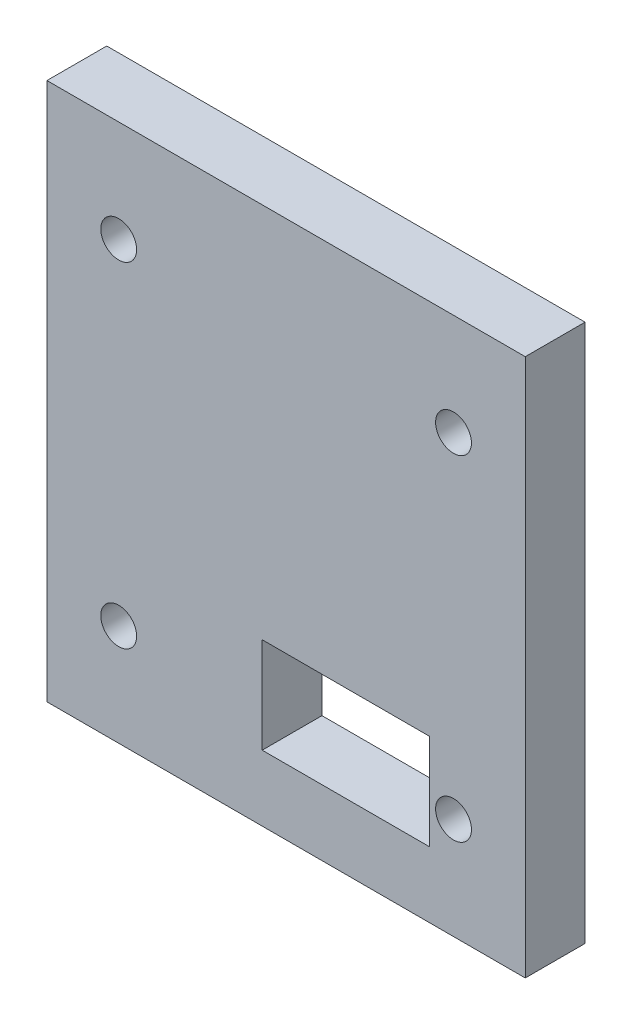
SolidWorks part; units mm, degrees
ref_plane "Front Plane" through (0, 0, 0) normal (0, 0, 1) x (1, 0, 0)
ref_plane "Top Plane" through (0, 0, 0) normal (0, 1, 0) x (1, 0, 0)
ref_plane "Right Plane" through (0, 0, 0) normal (1, 0, 0) x (0, 0, -1)
sketch "Sketch1" plane through (0, 0, 0) normal (0, 0, 1) x (1, 0, 0)
  line L1 (0, 0) -> (35, 0)
  line L2 (0, 0) -> (0, 45)
  line L3 (0, 45) -> (35, 45)
  line L4 (35, 0) -> (35, 45)
  dimension "D1" = 45
  dimension "D2" = 35
extrude "Boss-Extrude1" add sketch "Sketch1" along normal blind 5
sketch "Sketch2" plane through (0, 0, 0) normal (0, -1, 0) x (1, 0, 0)
  line L0 (0, 5) -> (35, 5) construction
  line L1 (0, 5) -> (0, 0) construction
  circle A0 centre (2, 2.5) radius 1.5
  circle A1 centre (33, 2.5) radius 1.5
  circle A2 centre (9.75, 2.5) radius 1.5
  circle A3 centre (25.25, 2.5) radius 1.5
  point P14 (0, 0)
  dimension "D1" = 3
  dimension "D2" = 2.5
  dimension "D3" = 2
  dimension "D4" = 31
  dimension "D5" = 7.75
  dimension "D6" = 7.75
extrude "Cut-Extrude1" cut sketch "Sketch2" against normal blind 5
sketch "Sketch4" plane through (35, 0, 0) normal (1, 0, 0) x (0, 0, -1)
  line L1 (-5, 45) -> (0, 45)
  line L2 (-5, 45) -> (-5, 0)
  line L3 (-5, 0) -> (0, 0)
  line L4 (0, 45) -> (0, 0)
extrude "Boss-Extrude2" add sketch "Sketch4" along normal blind 2.5
sketch "Sketch5" plane through (0, 0, 0) normal (-1, 0, 0) x (0, 0, 1)
  line L1 (0, 45) -> (5, 45)
  line L2 (0, 45) -> (0, 0)
  line L3 (0, 0) -> (5, 0)
  line L4 (5, 45) -> (5, 0)
extrude "Boss-Extrude3" add sketch "Sketch5" along normal blind 2.5
sketch "Sketch6" plane through (0, 0, 5) normal (0, 0, 1) x (1, 0, 0)
  line L0 (37.5, 45) -> (-2.5, 45) construction
  line L1 (-2.5, 0) -> (-2.5, 45) construction
  circle A0 centre (3.5, 36.5) radius 1.5
  circle A1 centre (31.5, 8.5) radius 1.5
  circle A2 centre (31.5, 36.5) radius 1.5
  circle A3 centre (3.5, 8.5) radius 1.5
  point P8 (0, 0)
  point P9 (0, 0)
  point P10 (0, 0)
  point P11 (0, 0)
  point P12 (0, 0)
  point P13 (30.7858, 37.0569)
  point P14 (2.5897, 5.5538)
  point P19 (0, 0)
  dimension "D1" = 3
  dimension "D2" = 28
  dimension "D3" = 28
  dimension "D4" = 8.5
  dimension "D5" = 6
extrude "Cut-Extrude2" cut sketch "Sketch6" against normal up to surface (5 mm away) up to face at (17.5, 22.5, 0)
sketch "Sketch7" plane through (0, 0, 5) normal (0, 0, 1) x (1, 0, 0)
  line L1 (15.5, 13.5) -> (29.5, 13.5)
  line L2 (15.5, 13.5) -> (15.5, 5.5)
  line L3 (15.5, 5.5) -> (29.5, 5.5)
  line L4 (29.5, 13.5) -> (29.5, 5.5)
  circle A1 centre (31.5, 8.5) radius 1.5 construction
  point P6 (5.5, 15.2552)
  dimension "D3" = 5
  dimension "D4" = 2
  dimension "D1" = 14
  dimension "D2" = 8
extrude "Cut-Extrude3" cut sketch "Sketch7" against normal up to surface (5 mm away) up to face at (2, 8.5, 0)
